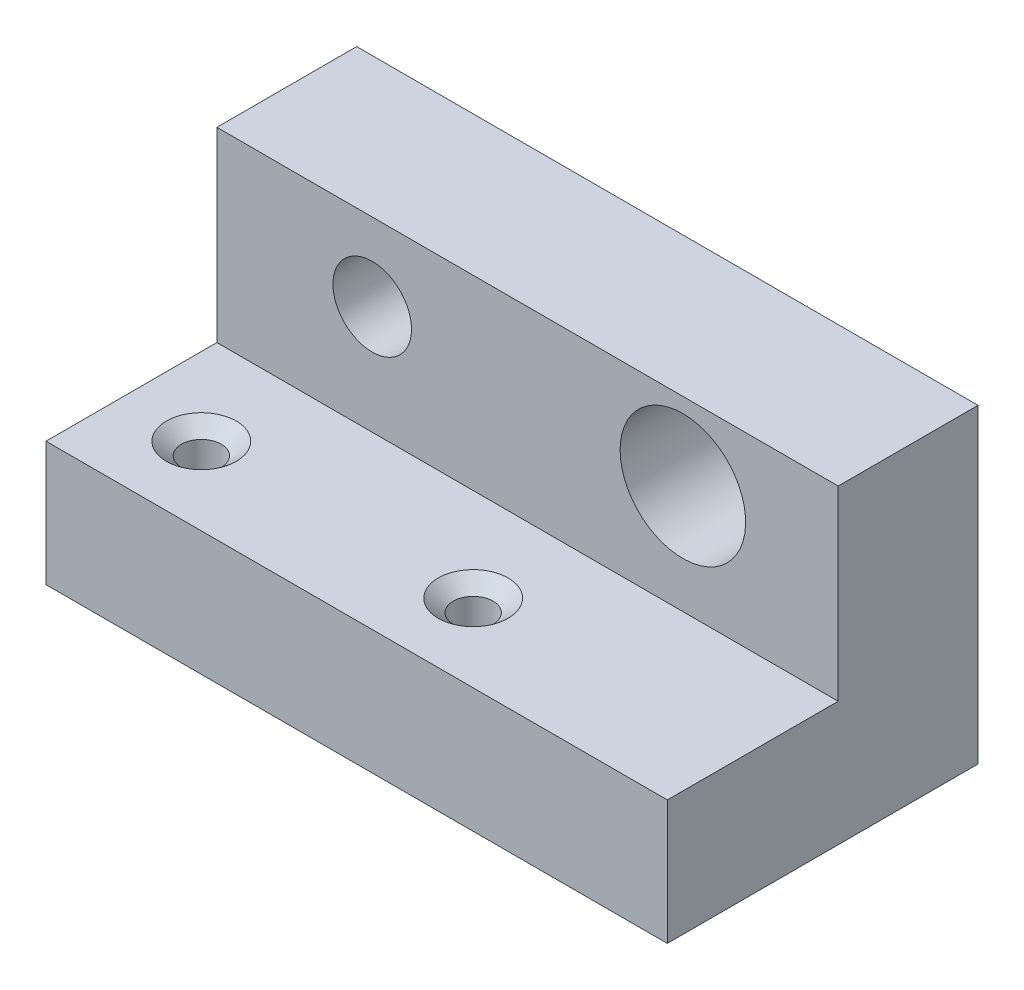
SolidWorks part; units mm, degrees
material "Delrin 2700 NC010, Low Viscosity Acetal Copolymer (SS)"
ref_plane "Front Plane" through (0, 0, 0) normal (0, 0, 1) x (1, 0, 0)
ref_plane "Top Plane" through (0, 0, 0) normal (0, 1, 0) x (1, 0, 0)
ref_plane "Right Plane" through (0, 0, 0) normal (1, 0, 0) x (0, 0, -1)
sketch "Sketch2" plane through (0, 0, 0) normal (1, 0, 0) x (0, 0, -1)
  line L0 (0, 0) -> (0, 10.16)
  line L1 (0, 10.16) -> (13.97, 10.16)
  line L2 (13.97, 10.16) -> (13.97, 25.4)
  line L3 (13.97, 25.4) -> (25.4, 25.4)
  line L4 (25.4, 25.4) -> (25.4, 0)
  line L5 (25.4, 0) -> (0, 0)
  dimension "D1" = 10.16
  dimension "D2" = 25.4
  dimension "D3" = 11.43
  dimension "D4" = 25.4
extrude "Boss-Extrude1" add sketch "Sketch2" along normal blind 50.8
sketch "Sketch3" plane through (0, 0, -13.97) normal (0, 0, 1) x (1, 0, 0)
  line L0 (50.8, 0) -> (0, 0) construction
  line L1 (50.8, 25.4) -> (50.8, 10.16) construction
  line L2 (25.4, 0) -> (25.4, 25.4) construction
  line L3 (50.8, 25.4) -> (0, 25.4) construction
  circle A0 centre (12.7, 19.05) radius 3.2131
  dimension "D1" = 6.4262
  dimension "D2" = 19.05
  dimension "D3" = 38.1
extrude "Cut-Extrude1" cut sketch "Sketch3" against normal through all
hole_wizard "CSK for #4 Flat Head Machine Screw (100)1" positions "Sketch5" profile "Sketch4" countersink size "#4" standard "ANSI Inch" end condition through all
sketch "Sketch5" plane through (0, 10.16, 0) normal (0, 1, 0) x (1, 0, 0)
  line L0 (0, 13.97) -> (0, 0) construction
  line L1 (50.8, 0) -> (0, 0) construction
  point P0 (6.35, 6.35)
  point P7 (28.575, 6.35)
  dimension "D1" = 6.35
  dimension "D2" = 6.35
  dimension "D3" = 22.225
  dimension "D4" = 6.35
sketch "Sketch4" plane through (6.35, 10.16, -6.35) normal (1, 0, 0) x (0, 0, 1)
  line L0 (0, 0) -> (0, 10.16)
  line L1 (0, 10.16) -> (1.6319, 10.16)
  line L2 (1.6319, 10.16) -> (1.6319, 1.0284)
  line L3 (1.6319, 1.0284) -> (2.8575, 0)
  line L5 (2.8575, 0) -> (0, 0)
  line L6 (-1.6319, 1.0284) -> (-2.8575, 0) construction
  line L11 (0, -6.35) -> (0, 107.95) construction
  dimension "Thru Hole Dia." = 3.2639
  dimension "Thru Hole Depth" = 10.16
  dimension "Near C'Sink Dia." = 5.715
  dimension "Near C'Sink Angle" = 100
hole_wizard "Y (0.404) Diameter Hole1" positions "Sketch8" profile "Sketch9" hole size "Y" standard "ANSI Inch" end condition through all
sketch "Sketch8" plane through (0, 0, -25.4) normal (0, 0, -1) x (-1, 0, 0)
  line L1 (-50.8, 0) -> (0, 0) construction
  circle A1 centre (-12.7, 19.05) radius 3.2131 construction
  point P0 (-38.1, 19.05)
  dimension "D1" = 19.05
  dimension "D2" = 25.4
sketch "Sketch9" plane through (38.1, 19.05, -25.4) normal (1, 0, 0) x (0, 1, 0)
  line L0 (0, 0) -> (0, 25.4)
  line L1 (0, 25.4) -> (5.1308, 25.4)
  line L2 (5.1308, 25.4) -> (5.1308, 0)
  line L5 (5.1308, 0) -> (0, 0)
  line L11 (0, -6.35) -> (0, 107.95) construction
  dimension "Thru Hole Dia." = 10.2616
  dimension "Thru Hole Depth" = 25.4
